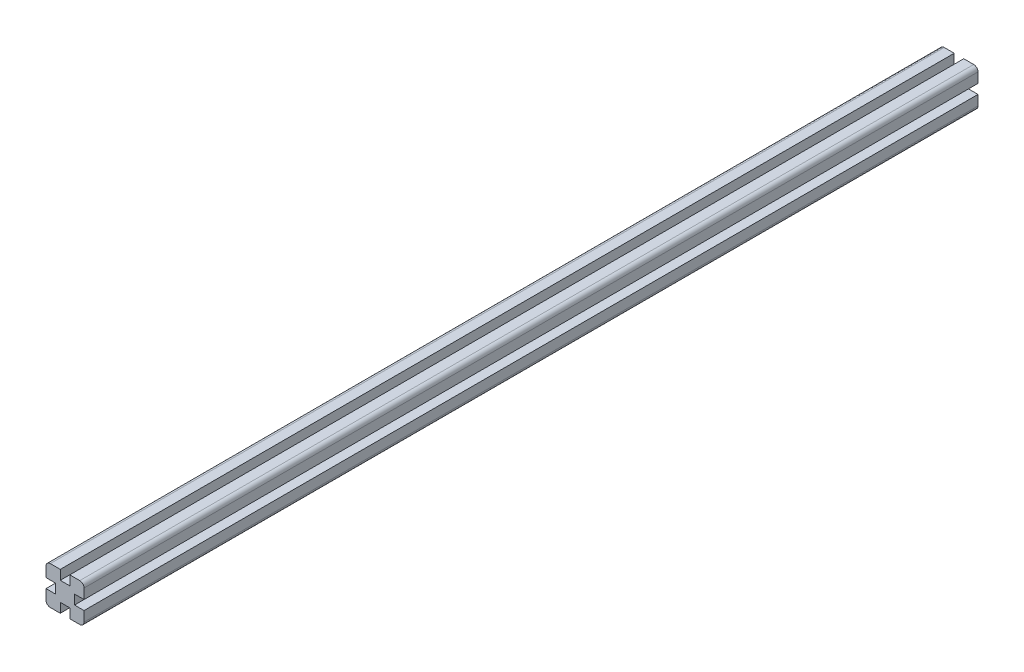
SolidWorks part; units mm, degrees
ref_plane "Front Plane" through (0, 0, 0) normal (0, 0, 1) x (1, 0, 0)
ref_plane "Top Plane" through (0, 0, 0) normal (0, 1, 0) x (1, 0, 0)
ref_plane "Right Plane" through (0, 0, 0) normal (1, 0, 0) x (0, 0, -1)
sketch "Sketch1" plane through (0, 0, 0) normal (0, 0, 1) x (1, 0, 0)
  line L0 (0, 0) -> (0, -50000) construction
  line L1 (-15.5, -20) -> (-5, -20)
  line L2 (-20, -15.5) -> (-20, -5)
  line L3 (-15.5, 20) -> (-15, 20)
  line L4 (20, -15.5) -> (20, -5)
  line L5 (-20, -20) -> (20, 20) construction
  line L6 (-20, 20) -> (20, -20) construction
  line L8 (-5, -20) -> (-5, -10)
  line L9 (-5, -10) -> (5, -10)
  line L10 (5, -20) -> (5, -10)
  line L15 (5, -20) -> (15.5, -20)
  line L16 (-8, 20) -> (-5, 20)
  line L18 (-15, 20) -> (-8, 20)
  line L19 (-20, 5) -> (-10, 5)
  line L20 (-10, 5) -> (-10, -5)
  line L21 (-20, -5) -> (-10, -5)
  line L22 (5, 20) -> (5, 10)
  line L23 (5, 10) -> (-5, 10)
  line L24 (-5, 20) -> (-5, 10)
  line L25 (20, -5) -> (10, -5)
  line L26 (10, -5) -> (10, 5)
  line L27 (20, 5) -> (10, 5)
  line L28 (-20, 5) -> (-20, 15.5)
  line L29 (5, 20) -> (15.5, 20)
  line L30 (20, 5) -> (20, 15.5)
  arc A0 (-20, 15.5) -> (-15.5, 20) centre (-15.5, 15.5) cw
  arc A1 (-15.5, -20) -> (-20, -15.5) centre (-15.5, -15.5) cw
  arc A2 (15.5, -20) -> (20, -15.5) centre (15.5, -15.5) ccw
  arc A3 (15.5, 20) -> (20, 15.5) centre (15.5, 15.5) cw
  point P0 (0, 0)
  point P41 (0, 0)
  dimension "D8" = 4.5
  dimension "D1" = 40
  dimension "D2" = 40
  dimension "D3" = 15
  dimension "D4" = 10
  dimension "D5" = 5
  dimension "D6" = 28
  dimension "D7" = 4
extrude "Boss-Extrude1" add sketch "Sketch1" along normal blind 940
